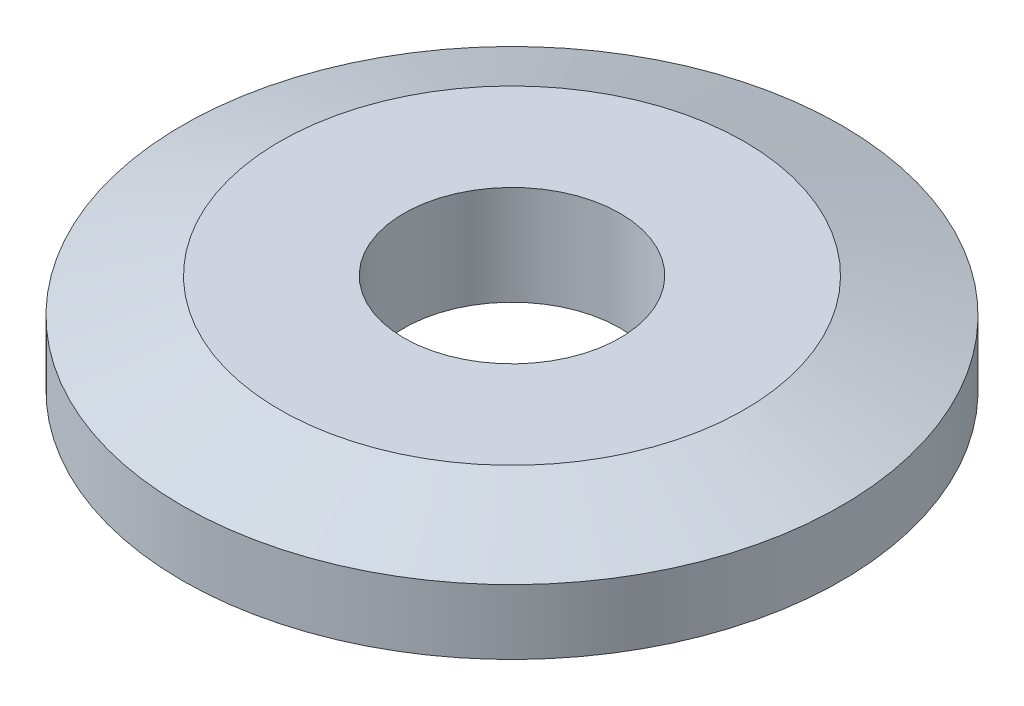
SolidWorks part; units mm, degrees
material "6061 Alloy"
ref_plane "Front Plane" through (0, 0, 0) normal (0, 0, 1) x (1, 0, 0)
ref_plane "Top Plane" through (0, 0, 0) normal (0, 1, 0) x (1, 0, 0)
ref_plane "Right Plane" through (0, 0, 0) normal (1, 0, 0) x (0, 0, -1)
sketch "Sketch1" plane through (0, 0, 0) normal (0, 0, 1) x (1, 0, 0)
  line L0 (0, 0) -> (0, 2.3368) construction
  line L1 (2.54, 0) -> (2.54, 2.3368)
  line L2 (2.54, 2.3368) -> (5.461, 2.3368)
  line L3 (5.461, 2.3368) -> (7.747, 1.524)
  line L4 (7.747, 1.524) -> (7.747, 0)
  line L5 (7.747, 0) -> (2.54, 0)
  dimension "D1" = 5.08
  dimension "D2" = 2.3368
  dimension "D3" = 15.494
  dimension "D4" = 10.922
  dimension "D5" = 1.524
revolve "Revolve1" add sketch "Sketch1" angle 360 about L0
